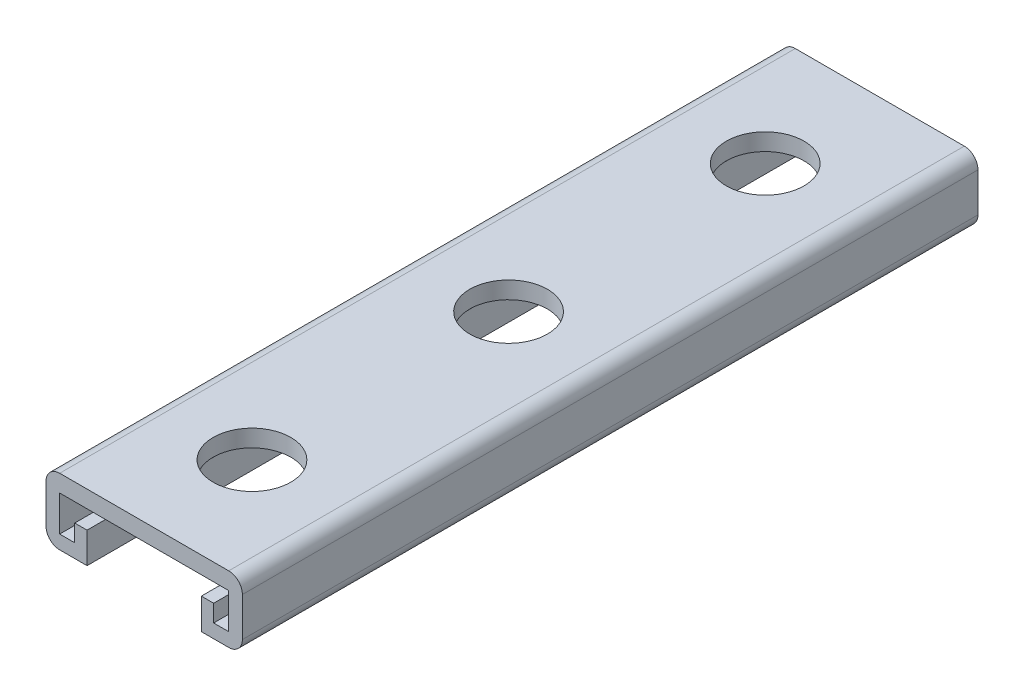
SolidWorks part; units mm, degrees
ref_plane "Płaszczyzna przednia" through (0, 0, 0) normal (0, 0, 1) x (1, 0, 0)
ref_plane "Płaszczyzna górna" through (0, 0, 0) normal (0, 1, 0) x (1, 0, 0)
ref_plane "Płaszczyzna prawa" through (0, 0, 0) normal (1, 0, 0) x (0, 0, -1)
sketch "Sketch1" plane through (0, 0, 0) normal (0, 0, 1) x (1, 0, 0)
  line L0 (-24.5, 0) -> (-24.5, -10)
  line L1 (-24.5, 0) -> (0, 0)
  line L2 (-24.5, -10) -> (-20.5, -10)
  line L3 (-20.5, -10) -> (-20.5, -5)
  line L4 (-20.5, -5) -> (-16.5, -5)
  line L5 (-16.5, -5) -> (-16.5, -10)
  line L6 (-16.5, -10) -> (0, -10)
  line L7 (0, 22.68) -> (0, -27.6471) construction
  line L9 (-24.7, 0.2) -> (0, 0.2)
  line L10 (-24.7, 0.2) -> (-24.7, -10.2)
  line L11 (-24.7, -10.2) -> (-20.3, -10.2)
  line L12 (-20.3, -10.2) -> (-20.3, -5.2)
  line L13 (-20.3, -5.2) -> (-16.7, -5.2)
  line L14 (-16.7, -5.2) -> (-16.7, -10)
  line L15 (-16.7, -10) -> (-16.7, -14.2)
  line L16 (-16.7, -14.2) -> (-28.7, -14.2)
  line L17 (-28.7, -14.2) -> (-28.7, 5.2)
  line L18 (-28.7, 5.2) -> (28.7, 5.2)
  line L19 (24.7, 0.2) -> (24.7, -10.2)
  line L20 (24.7, -10.2) -> (20.3, -10.2)
  line L21 (20.3, -10.2) -> (20.3, -5.2)
  line L22 (20.3, -5.2) -> (16.7, -5.2)
  line L23 (16.7, -5.2) -> (16.7, -10)
  line L24 (16.7, -10) -> (16.7, -14.2)
  line L25 (16.7, -14.2) -> (28.7, -14.2)
  line L26 (28.7, -14.2) -> (28.7, 5.2)
  line L27 (24.7, 0.2) -> (0, 0.2)
  point P12 (0, 5.2)
  dimension "D1" = 24.5
  dimension "D2" = 10
  dimension "D3" = 4
  dimension "D4" = 5
  dimension "D5" = 4
  dimension "D6" = 5
  dimension "D8" = 4
  dimension "D9" = 4
  dimension "D10" = 5
  dimension "D7" = 0.2
extrude "Boss-Extrude2" add sketch "Sketch1" along normal blind 213 contours L7 L18 L17 L16 L15 L14 L13 L12 L11 L10 L9 | L18 L7 L27 L19 L20 L21 L22 L23 L24 L25 L26
sketch "Sketch2" plane through (0, 0, 0) normal (0, 0, -1) x (-1, 0, 0)
  line L1 (-28.7, 5.2) -> (28.7, 5.2)
  line L2 (-28.7, 5.2) -> (-28.7, -14.2)
  line L3 (-28.7, -14.2) -> (28.7, -14.2)
  line L4 (28.7, 5.2) -> (28.7, -14.2)
extrude "Boss-Extrude3" add sketch "Sketch2" along normal blind 2
fillet "Fillet2" radius 4 4 edges at (-28.7, -14.2, 105.5) (28.7, -14.2, 105.5) (28.7, 5.2, 105.5) (-28.7, 5.2, 105.5)
sketch "Sketch3" plane through (0, 5.2, 0) normal (0, 1, 0) x (1, 0, 0)
  line L0 (0, 2) -> (0, -215.1388) construction
  line L1 (-24.7, 2) -> (24.7, 2) construction
  line L3 (-24.7, -213) -> (24.7, -213) construction
  circle A0 centre (0, -31.5) radius 11.35
  circle A1 centre (0, -106.5) radius 11.35
  circle A2 centre (0, -181.5) radius 11.35
  point P6 (0, 2)
  point P13 (0, 0)
  dimension "D2" = 22.7
  dimension "D1" = 31.5
  dimension "D3" = 3
extrude "Cut-Extrude1" cut sketch "Sketch3" against normal blind 59
